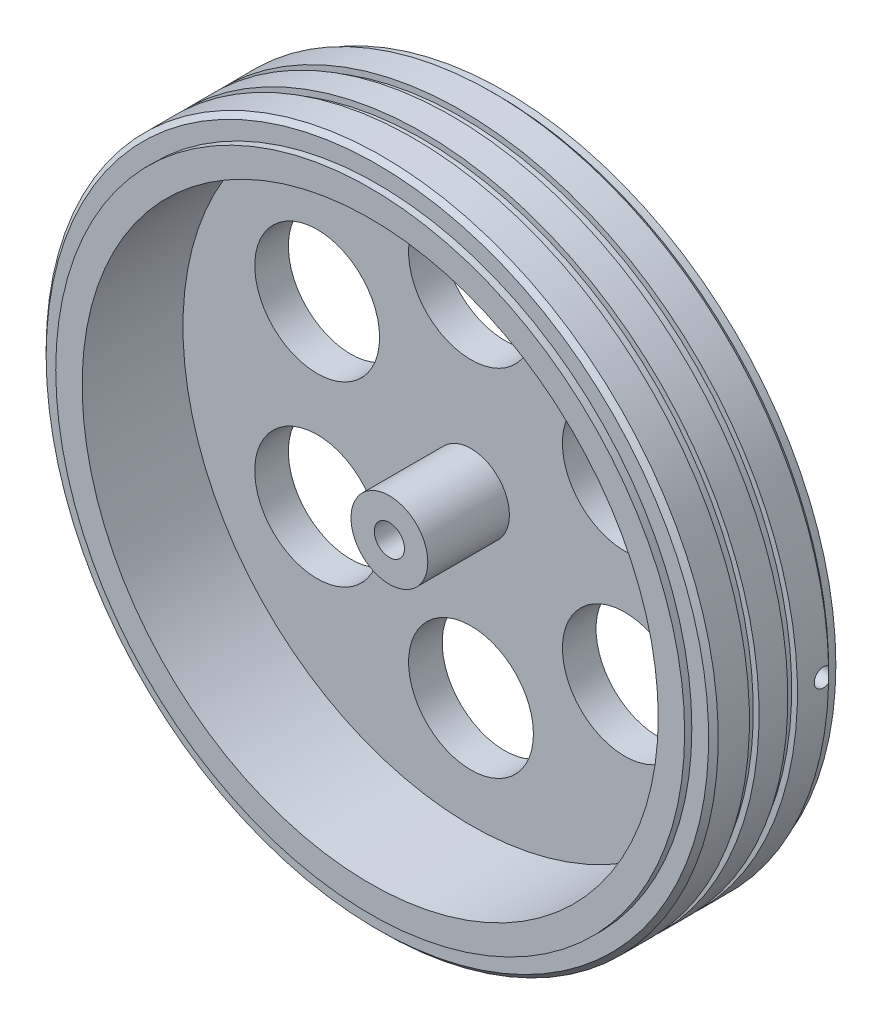
SolidWorks part; units mm, degrees
ref_plane "Front Plane" through (0, 0, 0) normal (0, 0, 1) x (1, 0, 0)
ref_plane "Top Plane" through (0, 0, 0) normal (0, 1, 0) x (1, 0, 0)
ref_plane "Right Plane" through (0, 0, 0) normal (1, 0, 0) x (0, 0, -1)
sketch "Sketch1" plane through (0, 0, 0) normal (0, 0, 1) x (1, 0, 0)
  circle A0 centre (0, 0) radius 64
  circle A1 centre (0, 0) radius 60
extrude "Rim" add sketch "Sketch1" along normal blind 28
sketch "Sketch2" plane through (0, 0, 0) normal (0, 0, 1) x (1, 0, 0)
  circle A0 centre (0, 0) radius 65.5
  circle A1 centre (0, 0) radius 63
extrude "Inner_bead_lip" add sketch "Sketch2" along normal blind 1.5
ref_plane "P_Front_26p5" through (0, 0, 26.5) normal (0, 0, 1) x (1, 0, 0)
sketch "Sketch3" plane through (0, 0, 26.5) normal (0, 0, 1) x (1, 0, 0)
  circle A0 centre (0, 0) radius 65.5
  circle A1 centre (0, 0) radius 63
extrude "Outer_bead_lip" add sketch "Sketch3" along normal blind 1.5
sketch "Sketch4" plane through (0, 0, 0) normal (0, 0, 1) x (1, 0, 0)
  circle A0 centre (0, 0) radius 61
extrude "Web" add sketch "Sketch4" along normal blind 7
sketch "Sketch5" plane through (0, 0, 0) normal (0, 0, 1) x (1, 0, 0)
  circle A0 centre (0, 0) radius 8
extrude "Hub_boss" add sketch "Sketch5" along normal blind 24
ref_plane "P_Front_m1" through (0, 0, -1) normal (0, 0, 1) x (1, 0, 0)
sketch "Sketch6" plane through (0, 0, -1) normal (0, 0, 1) x (1, 0, 0)
  circle A0 centre (32.0429, 18.5) radius 13
  circle A1 centre (0, 37) radius 13
  circle A2 centre (-32.0429, 18.5) radius 13
  circle A3 centre (-32.0429, -18.5) radius 13
  circle A4 centre (0, -37) radius 13
  circle A5 centre (32.0429, -18.5) radius 13
extrude "Lightening_holes" cut sketch "Sketch6" along normal blind 9
sketch "Sketch7" plane through (0, 0, -1) normal (0, 0, 1) x (1, 0, 0)
  circle A0 centre (0, 0) radius 3.15
extrude "Round_bore_6mm" cut sketch "Sketch7" along normal blind 30
sketch "Sketch8" plane through (0, 0, 0) normal (1, 0, 0) x (0, 0, -1)
  line L0 (-1.5, 64) -> (-26.5, 64)
  line L1 (-26.5, 64) -> (-26.5, 69)
  line L2 (-26.5, 69) -> (-25.5, 70)
  line L3 (-25.5, 70) -> (-19, 70)
  line L4 (-19, 70) -> (-19, 68.8)
  line L5 (-19, 68.8) -> (-17, 68.8)
  line L6 (-17, 68.8) -> (-17, 70)
  line L7 (-17, 70) -> (-11, 70)
  line L8 (-11, 70) -> (-11, 68.8)
  line L9 (-11, 68.8) -> (-9, 68.8)
  line L10 (-9, 68.8) -> (-9, 70)
  line L11 (-9, 70) -> (-2.5, 70)
  line L12 (-2.5, 70) -> (-1.5, 69)
  line L13 (-1.5, 69) -> (-1.5, 64)
  line L14 (0, 0) -> (-30, 0) construction
revolve "Tyre" add sketch "Sketch8" angle 360 about L14
sketch "Sketch9" plane through (0, 0, 0) normal (0, 0, 1) x (1, 0, 0)
  circle A0 centre (0, 0) radius 69
  circle A1 centre (0, 0) radius 64
extrude "Bed_ring" add sketch "Sketch9" along normal blind 1.5
sketch "Sketch10" plane through (0, 0, 0) normal (1, 0, 0) x (0, 0, -1)
  circle A0 centre (-3.6, 0) radius 1.3
extrude "Grub_screw_M3" cut sketch "Sketch10" along normal blind 9
ref_plane "P_Right_8p5" through (8.5, 0, 0) normal (1, 0, 0) x (0, 0, -1)
sketch "Sketch11" plane through (8.5, 0, 0) normal (1, 0, 0) x (0, 0, -1)
  circle A0 centre (-3.6, 0) radius 1.9
extrude "Grub_key_access" cut sketch "Sketch11" along normal blind 62.5
